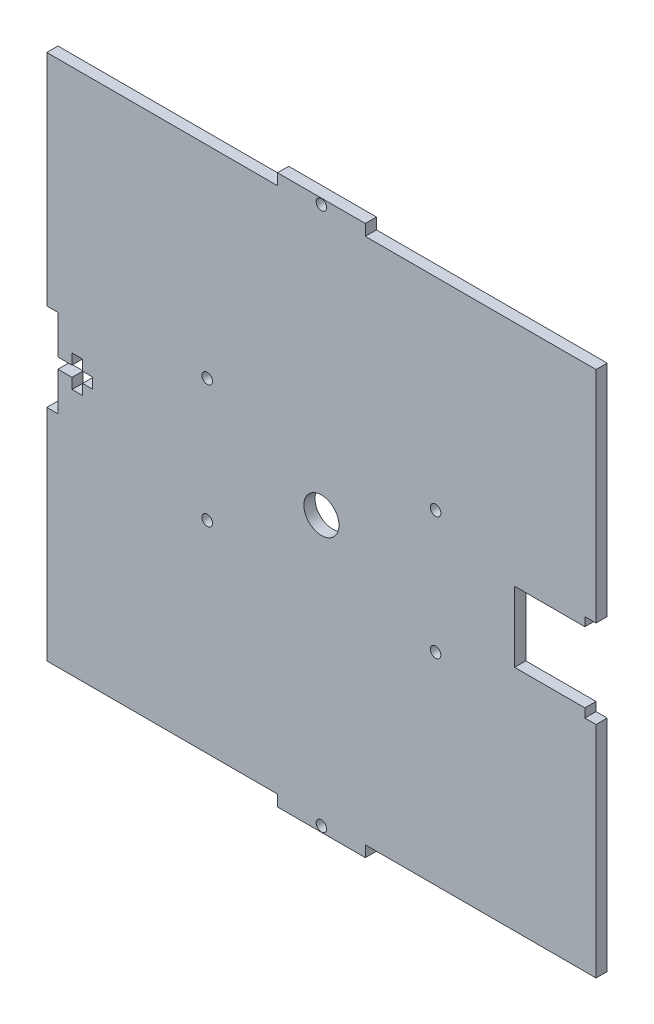
SolidWorks part; units mm, degrees
ref_plane "Front Plane" through (0, 0, 0) normal (0, 0, 1) x (1, 0, 0)
ref_plane "Top Plane" through (0, 0, 0) normal (0, 1, 0) x (1, 0, 0)
ref_plane "Right Plane" through (0, 0, 0) normal (1, 0, 0) x (0, 0, -1)
sketch "Sketch1" plane through (0, 0, 0) normal (0, 0, 1) x (1, 0, 0)
  line L0 (-12.5, 25) -> (12.5, 25) construction
  line L1 (-78.18, 75) -> (-12.5, 75)
  line L2 (-78.18, 75) -> (-78.18, 12.5)
  line L3 (-78.18, -75) -> (-12.5, -75)
  line L4 (78.18, 75) -> (78.18, 12.5)
  line L5 (-78.18, 75) -> (78.18, -75) construction
  line L6 (-78.18, -75) -> (78.18, 75) construction
  line L11 (12.5, 75) -> (12.5, 78.18)
  line L12 (12.5, 78.18) -> (-12.5, 78.18)
  line L17 (-12.5, 75) -> (-12.5, 78.18)
  line L18 (12.5, 75) -> (78.18, 75)
  line L25 (0, 100) -> (0, -75) construction
  line L26 (-100, 0) -> (100, 0) construction
  line L27 (-75, -1.5) -> (-75, -12.5)
  line L28 (-75, 12.5) -> (-78.18, 12.5)
  line L29 (-75, 12.5) -> (-75, 1.5)
  line L30 (-75, -12.5) -> (-78.18, -12.5)
  line L32 (-75, 12.5) -> (-78.18, -12.5) construction
  line L33 (-75, -12.5) -> (-78.18, 12.5) construction
  line L34 (-65.18, 1.5) -> (-68, 1.5)
  line L35 (-65.18, 1.5) -> (-65.18, -1.5)
  line L36 (-65.18, -1.5) -> (-68, -1.5)
  line L38 (-65.18, 1.5) -> (-75, -1.5) construction
  line L39 (-65.18, -1.5) -> (-75, 1.5) construction
  line L44 (-71, 4.5) -> (-68, 4.5)
  line L45 (-71, 4.5) -> (-71, 1.5)
  line L46 (-71, -4.5) -> (-68, -4.5)
  line L47 (-68, 4.5) -> (-68, 1.5)
  line L48 (-71, 4.5) -> (-68, -4.5) construction
  line L49 (-71, -4.5) -> (-68, 4.5) construction
  line L50 (-71, -1.5) -> (-71, -4.5)
  line L51 (-68, -1.5) -> (-68, -4.5)
  line L52 (-71, 1.5) -> (-75, 1.5)
  line L53 (-71, -1.5) -> (-75, -1.5)
  line L54 (65.18, 1.5) -> (68, 1.5)
  line L55 (68, 4.5) -> (68, 1.5)
  line L56 (71, 4.5) -> (68, 4.5)
  line L57 (71, 4.5) -> (71, 1.5)
  line L58 (71, 1.5) -> (75, 1.5)
  line L59 (75, 12.5) -> (75, 1.5)
  line L60 (75, 12.5) -> (78.18, 12.5)
  line L62 (75, -12.5) -> (78.18, -12.5)
  line L63 (75, -1.5) -> (75, -12.5)
  line L64 (71, -1.5) -> (75, -1.5)
  line L65 (71, -1.5) -> (71, -4.5)
  line L66 (71, -4.5) -> (68, -4.5)
  line L67 (68, -1.5) -> (68, -4.5)
  line L68 (65.18, -1.5) -> (68, -1.5)
  line L69 (65.18, 1.5) -> (65.18, -1.5)
  line L70 (-78.18, -12.5) -> (-78.18, -75)
  line L71 (78.18, -12.5) -> (78.18, -75)
  line L72 (0, -78.18) -> (0, -75) construction
  line L74 (12.5, -75) -> (12.5, -78.18)
  line L75 (12.5, -78.18) -> (-12.5, -78.18)
  line L76 (-12.5, -75) -> (-12.5, -78.18)
  line L77 (12.5, -76.59) -> (-12.5, -76.59) construction
  line L78 (12.5, -75) -> (78.18, -75)
  circle A2 centre (0, -76.59) radius 1.5
  circle A3 centre (0, 76.59) radius 1.5
  point P0 (0, 0)
  point P6 (-50, 50)
  point P11 (50, 50)
  point P16 (0, 0)
  point P27 (0, 25)
  point P30 (-76.59, 0)
  point P35 (-70.09, 0)
  point P40 (-70.09, 0)
  point P41 (-69.5, 0)
  dimension "D13" = 25
  dimension "D23" = 3
  dimension "D1" = 150
  dimension "D2" = 156.36
  dimension "D3" = 9
  dimension "D9" = 50
  dimension "D10" = 50
  dimension "D14" = 50
  dimension "D15" = 25
  dimension "D16" = 13
  dimension "D17" = 3.18
  dimension "D18" = 3
  dimension "D19" = 4
  dimension "D20" = 3
  dimension "D21" = 3.18
  dimension "D22" = 25
extrude "Boss-Extrude1" add sketch "Sketch1" along normal blind 3.18
sketch "Sketch2" plane through (0, 0, 3.18) normal (0, 0, 1) x (1, 0, 0)
  line L0 (-65.18, 0) -> (65.18, 0) construction
  line L1 (-65.18, 1.5) -> (-65.18, -1.5) construction
  line L2 (65.18, -1.5) -> (65.18, 1.5) construction
  line L3 (0, 78.18) -> (0, -78.18) construction
  line L4 (12.5, 78.18) -> (-12.5, 78.18) construction
  line L5 (-12.5, -78.18) -> (12.5, -78.18) construction
  line L6 (32.5, 17.5) -> (32.5, -17.5) construction
  line L7 (32.5, -17.5) -> (-32.5, -17.5) construction
  line L8 (-32.5, -17.5) -> (-32.5, 17.5) construction
  line L9 (-32.5, 17.5) -> (32.5, 17.5) construction
  circle A0 centre (32.5, 17.5) radius 1.5
  circle A1 centre (32.5, -17.5) radius 1.5
  circle A2 centre (-32.5, 17.5) radius 1.5
  circle A3 centre (-32.5, -17.5) radius 1.5
  point P20 (32.5, 0)
  point P21 (0, 17.5)
  dimension "D1" = 3
  dimension "D2" = 3
  dimension "D3" = 3
  dimension "D4" = 3
  dimension "D5" = 65
  dimension "D6" = 35
  dimension "D7" = 35
  dimension "D8" = 65
extrude "Cut-Extrude1" cut sketch "Sketch2" against normal blind 10
sketch "Sketch3" plane through (0, 0, 3.18) normal (0, 0, 1) x (1, 0, 0)
  circle A0 centre (0, 0) radius 5
  dimension "D1" = 10
extrude "Cut-Extrude2" cut sketch "Sketch3" against normal blind 10
sketch "Sketch4" plane through (0, 0, 3.18) normal (0, 0, 1) x (1, 0, 0)
  line L0 (75, 1.5) -> (75, 12.5) construction
  line L1 (75, 10) -> (55, 10)
  line L2 (75, 10) -> (75, -10)
  line L3 (75, -10) -> (55, -10)
  line L4 (55, 10) -> (55, -10)
  line L5 (55, 0) -> (75, 0) construction
  line L6 (78.18, 0) -> (-78.18, 0) construction
  line L7 (78.18, 12.5) -> (78.18, -12.5) construction
  line L8 (-78.18, -12.5) -> (-78.18, 12.5) construction
  dimension "D1" = 20
  dimension "D2" = 20
extrude "Cut-Extrude3" cut sketch "Sketch4" against normal blind 10
